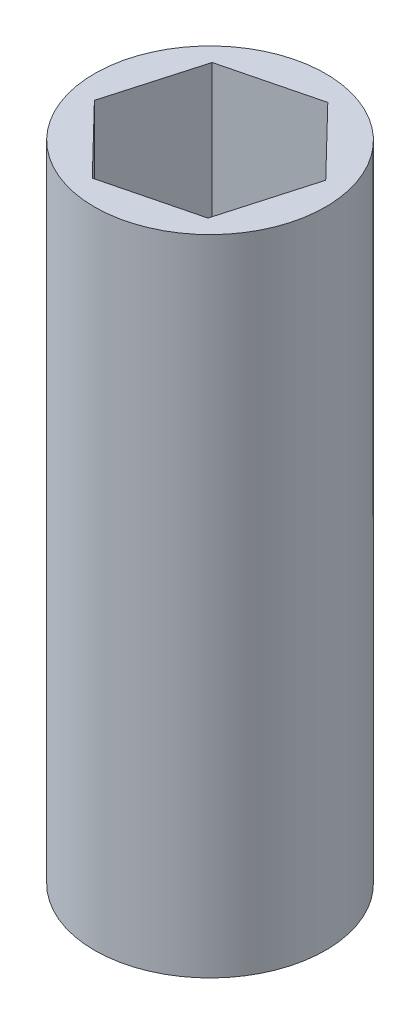
SolidWorks part; units mm, degrees
ref_plane "Front Plane" through (0, 0, 0) normal (0, 0, 1) x (1, 0, 0)
ref_plane "Top Plane" through (0, 0, 0) normal (0, 1, 0) x (1, 0, 0)
ref_plane "Right Plane" through (0, 0, 0) normal (1, 0, 0) x (0, 0, -1)
sketch "Sketch1" plane through (0, 0, 0) normal (0, 1, 0) x (1, 0, 0)
  line L1 (2.0076, 7.0522) -> (-5.1036, 5.2647)
  line L2 (-5.1036, 5.2647) -> (-7.1111, -1.7875)
  line L3 (-7.1111, -1.7875) -> (-2.0076, -7.0522)
  line L4 (-2.0076, -7.0522) -> (5.1036, -5.2647)
  line L5 (5.1036, -5.2647) -> (7.1111, 1.7875)
  line L6 (7.1111, 1.7875) -> (2.0076, 7.0522)
  circle A0 centre (0, 0) radius 6.35 construction
  circle A1 centre (0, 0) radius 8.89
  dimension "D2" = 17.78
  dimension "D1" = 12.7
extrude "Boss-Extrude1" add sketch "Sketch1" along normal blind 49.53
